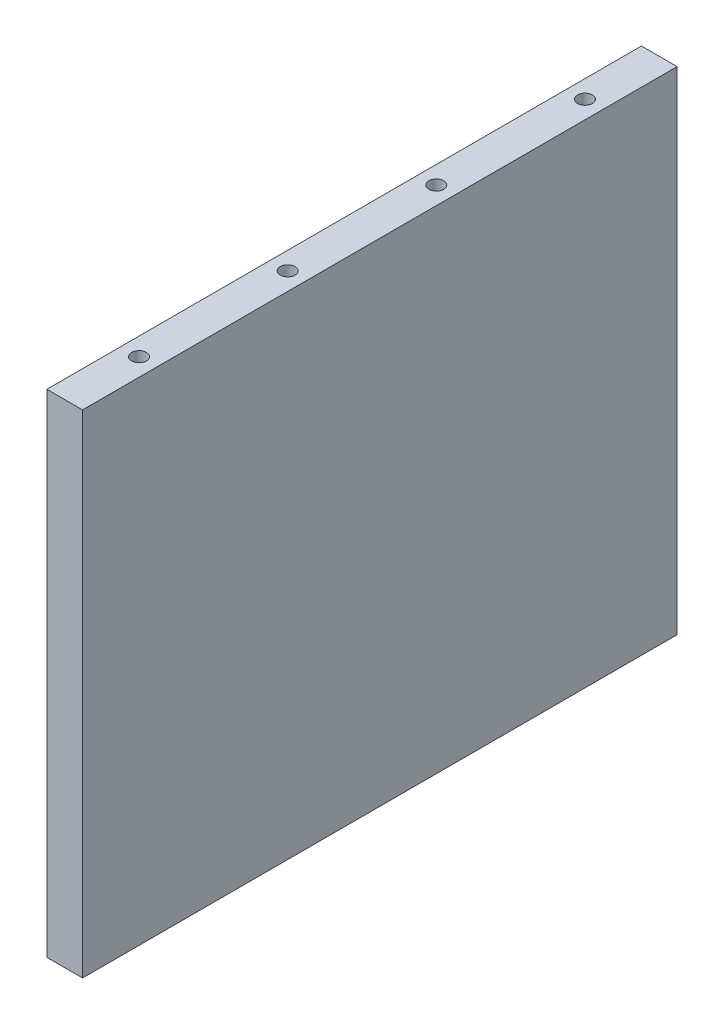
SolidWorks part; units mm, degrees
ref_plane "Front Plane" through (0, 0, 0) normal (0, 0, 1) x (1, 0, 0)
ref_plane "Top Plane" through (0, 0, 0) normal (0, 1, 0) x (1, 0, 0)
ref_plane "Right Plane" through (0, 0, 0) normal (1, 0, 0) x (0, 0, -1)
sketch "Sketch1" plane through (0, 0, 0) normal (0, 0, 1) x (1, 0, 0)
  line L0 (-119, 208) -> (-131, 208)
  line L1 (-119, 165) -> (-119, 208)
  line L2 (0, 208) -> (-148, 208) construction
  line L3 (-119, 165) -> (-119, 42.5)
  line L4 (-148, 42.5) -> (0, 42.5) construction
  line L5 (-119, 42.5) -> (-131, 42.5)
  line L6 (-131, 42.5) -> (-131, 208)
extrude "Boss-Extrude1" add sketch "Sketch1" along normal up to surface (200 mm away)
sketch "Sketch2" plane through (0, 208, 0) normal (0, 1, 0) x (1, 0, 0)
  circle A0 centre (-125, -25) radius 2.5
  circle A1 centre (-125, -75) radius 2.5
  circle A2 centre (-125, -125) radius 2.5
  circle A3 centre (-125, -175) radius 2.5
  dimension "D1" = 4
sketch "Sketch3" plane through (0, 42.5, 0) normal (0, -1, 0) x (1, 0, 0)
  circle A0 centre (-125, 175) radius 2.5 construction
  circle A1 centre (-125, 125) radius 2.5 construction
  circle A2 centre (-125, 75) radius 2.5 construction
  circle A3 centre (-125, 25) radius 2.5 construction
  circle A4 centre (-125, 175) radius 2.5
  circle A5 centre (-125, 125) radius 2.5
  circle A6 centre (-125, 75) radius 2.5
  circle A7 centre (-125, 25) radius 2.5
extrude "Cut-Extrude2" cut sketch "Sketch2" against normal blind 15
extrude "Cut-Extrude3" cut sketch "Sketch3" against normal blind 15
